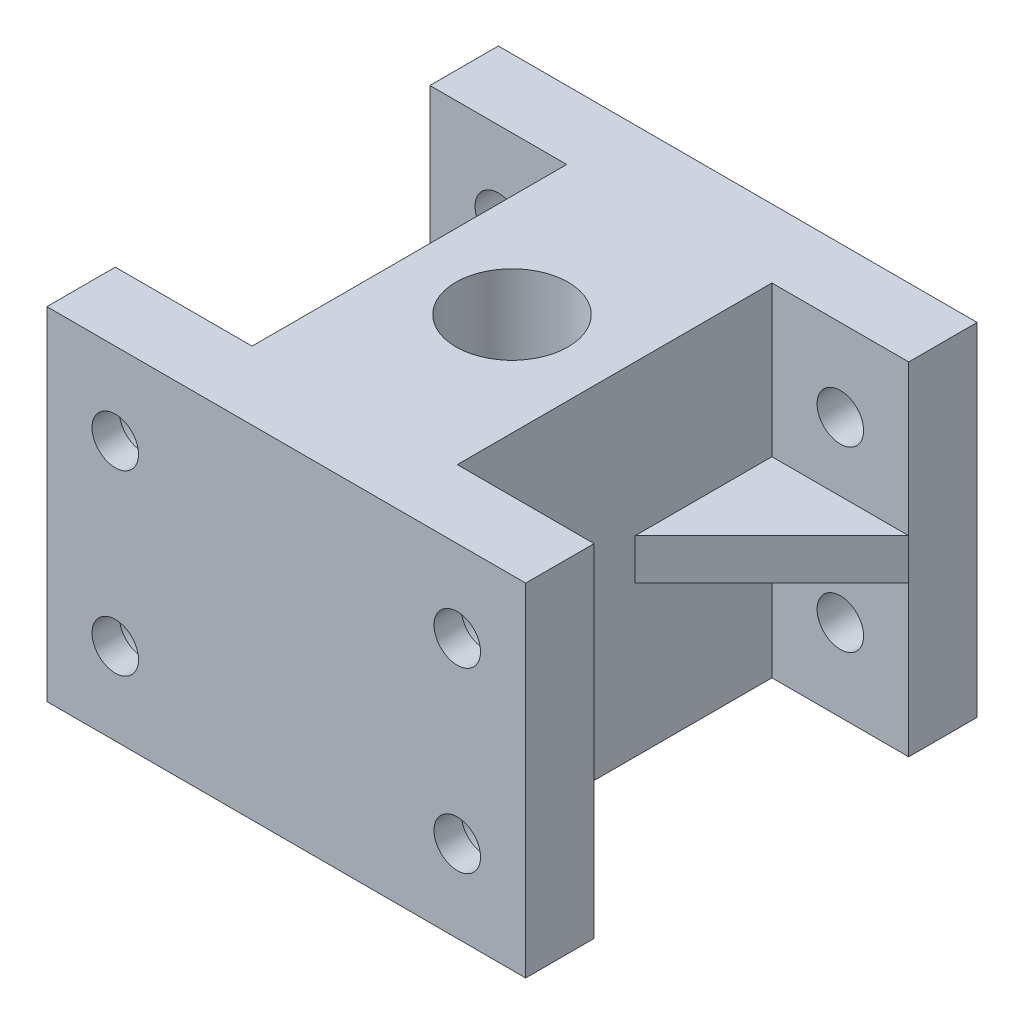
SolidWorks part; units mm, degrees
material "Custom Plastic"
ref_plane "Front Plane" through (0, 0, 0) normal (0, 0, 1) x (1, 0, 0)
ref_plane "Top Plane" through (0, 0, 0) normal (0, 1, 0) x (1, 0, 0)
ref_plane "Right Plane" through (0, 0, 0) normal (1, 0, 0) x (0, 0, -1)
sketch "Sketch1" plane through (0, 0, 0) normal (0, 0, 1) x (1, 0, 0)
  line L0 (-40.7762, 210.9236) -> (-10.7762, 210.9236) construction
  line L1 (-2.3262, 229.9236) -> (-7.3262, 229.9236) construction
  line L4 (264.0238, 210.9236) -> (264.0238, 235.9236)
  line L5 (264.0238, 235.9236) -> (-40.7762, 235.9236)
  line L6 (-40.7762, 235.9236) -> (-40.7762, 210.9236)
  line L7 (-40.7762, 210.9236) -> (264.0238, 210.9236)
  line L8 (264.0238, 210.9236) -> (264.0238, 235.9236)
  line L10 (-40.7762, 235.9236) -> (-40.7762, 210.9236)
  line L14 (-7.3262, 229.9236) -> (-7.3262, 210.9236) construction
  line L16 (-7.3262, 210.9236) -> (27.6738, 210.9236)
  line L17 (-7.3262, 210.9236) -> (-7.3262, 235.9236)
  line L18 (-7.3262, 235.9236) -> (27.6738, 235.9236)
  line L19 (27.6738, 210.9236) -> (27.6738, 235.9236)
  line L20 (-2.3262, 229.9236) -> (27.6738, 229.9236) construction
  line L21 (-2.3262, 216.9236) -> (27.6738, 216.9236) construction
  line L22 (27.6738, 229.9236) -> (22.6738, 229.9236) construction
  line L23 (22.6738, 229.9236) -> (22.6738, 216.9236) construction
  circle A0 centre (-2.3262, 216.9236) radius 1.7 construction
  circle A1 centre (-2.3262, 229.9236) radius 1.7 construction
  circle A2 centre (-2.3262, 216.9236) radius 1.7
  circle A3 centre (-2.3262, 229.9236) radius 1.7
  circle A4 centre (22.6738, 229.9236) radius 1.7
  circle A5 centre (22.6738, 216.9236) radius 1.7
  dimension "D1" = 0
extrude "Boss-Extrude1" add sketch "Sketch1" along normal blind 5 contours L16 L19 L18 L17 A5 A4 A3 A2
sketch "Sketch3" plane through (0, 210.9236, 0) normal (0, -1, 0) x (1, 0, 0)
  line L0 (-40.7762, 33) -> (264.0238, 33) construction
  line L1 (-40.7762, 33) -> (264.0238, 33)
  line L2 (-7.3262, 5) -> (2.6738, 5)
  line L3 (-7.3262, 33) -> (27.6738, 33)
  line L4 (-7.3262, 33) -> (-7.3262, 28)
  line L5 (-7.3262, 28) -> (27.6738, 28)
  line L6 (-7.3262, 0) -> (27.6738, 0)
  line L7 (27.6738, 0) -> (27.6738, 5)
  line L8 (27.6738, 5) -> (-7.3262, 5)
  line L9 (-7.3262, 5) -> (-7.3262, 0)
  line L10 (-7.3262, 0) -> (27.6738, 0)
  line L11 (27.6738, 0) -> (27.6738, 5)
  line L13 (-7.3262, 5) -> (-7.3262, 0)
  line L14 (27.6738, 33) -> (27.6738, 28)
  line L15 (27.6738, 5) -> (17.6738, 5)
  line L16 (2.6738, 16.5) -> (17.6738, 16.5) construction
  line L17 (2.6738, 5) -> (17.6738, 5)
  line L18 (2.6738, 5) -> (2.6738, 28)
  line L19 (2.6738, 28) -> (17.6738, 28)
  line L20 (17.6738, 5) -> (17.6738, 28)
  circle A0 centre (10.1738, 16.5) radius 4.1
  point P17 (2.6738, 16.5)
  line M10 (27.6738, 5) -> (-7.3262, 5)
  dimension "D1" = 0
extrude "Boss-Extrude2" add sketch "Sketch3" against normal up to surface (25 mm away) contours L18 L16 A0 L20 L5 | L16 L18 L20 A0 M10 | L14 L1 L4 L5 up to face at (10.1738, 235.9236, 2.5)
sketch "Sketch4" plane through (0, 0, 28) normal (0, 0, -1) x (-1, 0, 0)
  circle A0 centre (-22.6738, 229.9236) radius 1.7 construction
  circle A1 centre (-22.6738, 216.9236) radius 1.7 construction
  circle A2 centre (2.3262, 229.9236) radius 1.7 construction
  circle A3 centre (2.3262, 216.9236) radius 1.7 construction
  circle A4 centre (-22.6738, 229.9236) radius 1.7
  circle A5 centre (-22.6738, 216.9236) radius 1.7
  circle A6 centre (2.3262, 229.9236) radius 1.7
  circle A7 centre (2.3262, 216.9236) radius 1.7
extrude "Cut-Extrude1" cut sketch "Sketch4" against normal blind 5
sketch "Sketch5" plane through (0, 0, 28) normal (0, 0, -1) x (-1, 0, 0)
  circle A0 centre (-22.6738, 229.9236) radius 1.7 construction
  circle A1 centre (-22.6738, 216.9236) radius 1.7 construction
  circle A2 centre (2.3262, 229.9236) radius 1.7 construction
  circle A3 centre (2.3262, 216.9236) radius 1.7 construction
  circle A4 centre (-22.6738, 229.9236) radius 1.7
  circle A5 centre (-22.6738, 216.9236) radius 1.7
  circle A6 centre (2.3262, 229.9236) radius 1.7
  circle A7 centre (2.3262, 216.9236) radius 1.7
  circle A8 centre (2.3262, 216.9236) radius 3
  circle A9 centre (2.3262, 229.9236) radius 3
  circle A10 centre (-22.6738, 216.9236) radius 3
  circle A11 centre (-22.6738, 229.9236) radius 3
extrude "Cut-Extrude3" cut sketch "Sketch5" against normal blind 3
sketch "Sketch6" plane through (0, 210.9236, 0) normal (0, -1, 0) x (1, 0, 0)
  line L12 (-7.3262, 0) -> (27.6738, 0)
  line L13 (27.6738, 0) -> (27.6738, 5)
  line L14 (27.6738, 5) -> (17.6738, 5)
  line L15 (17.6738, 5) -> (17.6738, 28)
  line L16 (17.6738, 28) -> (27.6738, 28)
  line L17 (27.6738, 28) -> (27.6738, 33)
  line L18 (27.6738, 33) -> (-7.3262, 33)
  line L19 (-7.3262, 33) -> (-7.3262, 28)
  line L20 (-7.3262, 28) -> (2.6738, 28)
  line L21 (2.6738, 28) -> (2.6738, 5)
  line L22 (2.6738, 5) -> (-7.3262, 5)
  line L23 (-7.3262, 5) -> (-7.3262, 0)
  line L24 (-7.3262, 0) -> (27.6738, 0)
  line L25 (27.6738, 0) -> (27.6738, 5)
  line L26 (27.6738, 5) -> (17.6738, 5)
  line L27 (17.6738, 5) -> (17.6738, 28)
  line L28 (17.6738, 28) -> (27.6738, 28)
  line L29 (27.6738, 28) -> (27.6738, 33)
  line L30 (27.6738, 33) -> (-7.3262, 33)
  line L31 (-7.3262, 33) -> (-7.3262, 28)
  line L32 (-7.3262, 28) -> (2.6738, 28)
  line L33 (2.6738, 28) -> (2.6738, 5)
  line L34 (2.6738, 5) -> (-7.3262, 5)
  line L35 (-7.3262, 5) -> (-7.3262, 0)
  dimension "D1" = 0
extrude "Boss-Extrude3" add sketch "Sketch6" against normal blind 2
ref_plane "Plane1" through (0, 223.4236, 0) normal (0, 1, 0) x (1, 0, 0)
sketch "Sketch7" plane through (0, 223.4236, 0) normal (0, 1, 0) x (1, 0, 0)
  line L0 (-7.3262, -28) -> (2.6738, -18)
  line L1 (-7.3262, -5) -> (2.6738, -15)
  line L2 (27.6738, -28) -> (17.6738, -18)
  line L3 (27.6738, -5) -> (17.6738, -15)
  line L12 (27.6738, 0) -> (-7.3262, 0)
  line L13 (-7.3262, 0) -> (-7.3262, -5)
  line L14 (-7.3262, -5) -> (2.6738, -5)
  line L15 (2.6738, -5) -> (2.6738, -28)
  line L16 (2.6738, -28) -> (-7.3262, -28)
  line L17 (-7.3262, -28) -> (-7.3262, -33)
  line L18 (-7.3262, -33) -> (27.6738, -33)
  line L19 (27.6738, -33) -> (27.6738, -28)
  line L20 (27.6738, -28) -> (17.6738, -28)
  line L21 (17.6738, -28) -> (17.6738, -5)
  line L22 (17.6738, -5) -> (27.6738, -5)
  line L23 (27.6738, -5) -> (27.6738, 0)
  line L24 (27.6738, 0) -> (-7.3262, 0)
  line L25 (-7.3262, 0) -> (-7.3262, -5)
  line L26 (-7.3262, -5) -> (2.6738, -5)
  line L27 (2.6738, -5) -> (2.6738, -28)
  line L28 (2.6738, -28) -> (-7.3262, -28)
  line L29 (-7.3262, -28) -> (-7.3262, -33)
  line L30 (-7.3262, -33) -> (27.6738, -33)
  line L31 (27.6738, -33) -> (27.6738, -28)
  line L32 (27.6738, -28) -> (17.6738, -28)
  line L33 (17.6738, -28) -> (17.6738, -5)
  line L34 (17.6738, -5) -> (27.6738, -5)
  line L35 (27.6738, -5) -> (27.6738, 0)
  dimension "D1" = 0
extrude "Boss-Extrude4" add sketch "Sketch7" along normal mid plane 3 contours L33 L32 L2 | L34 L33 L3 | L27 L26 L1 | L28 L27 L0
